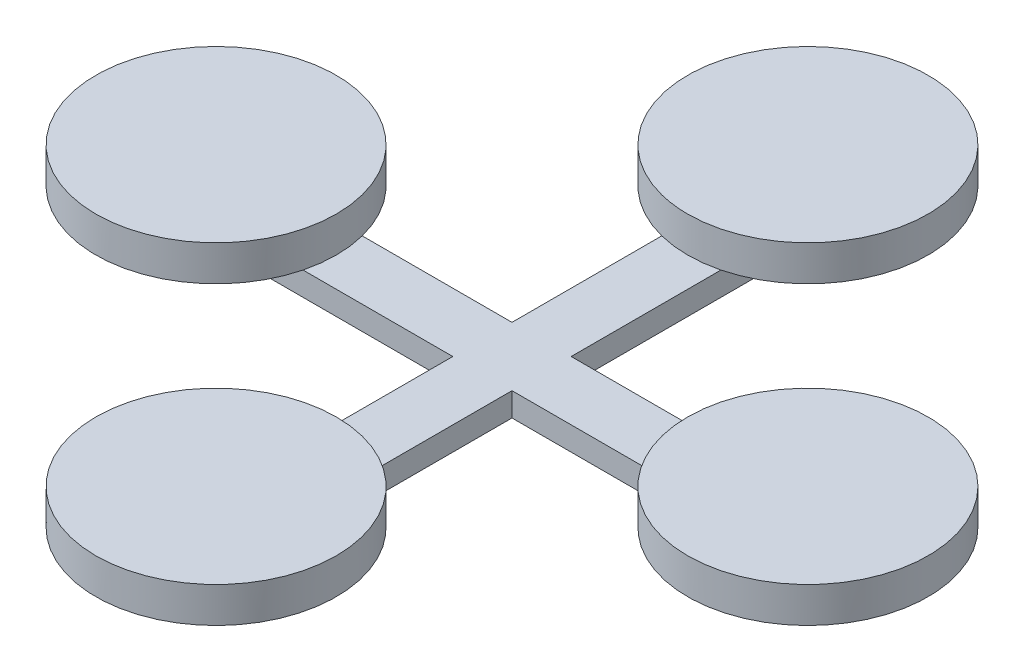
SolidWorks part; units mm, degrees
ref_plane "Front Plane" through (0, 0, 0) normal (0, 0, 1) x (1, 0, 0)
ref_plane "Top Plane" through (0, 0, 0) normal (0, 1, 0) x (1, 0, 0)
ref_plane "Right Plane" through (0, 0, 0) normal (1, 0, 0) x (0, 0, -1)
sketch "Sketch1" plane through (0, 0, 0) normal (0, 1, 0) x (1, 0, 0)
  line L1 (-12.5, 125) -> (12.5, 125)
  line L2 (-12.5, 125) -> (-12.5, -125)
  line L3 (-12.5, -125) -> (12.5, -125)
  line L4 (12.5, 125) -> (12.5, -125)
  line L5 (-12.5, 125) -> (12.5, -125) construction
  line L6 (-12.5, -125) -> (12.5, 125) construction
  line L7 (-125, 12.5) -> (125, 12.5)
  line L8 (-125, 12.5) -> (-125, -12.5)
  line L9 (-125, -12.5) -> (125, -12.5)
  line L10 (125, 12.5) -> (125, -12.5)
  line L11 (-125, 12.5) -> (125, -12.5) construction
  line L12 (-125, -12.5) -> (125, 12.5) construction
  point P0 (0, 0)
  point P6 (0, 0)
  dimension "D1" = 250
  dimension "D2" = 250
  dimension "D3" = 25
extrude "Boss-Extrude1" add sketch "Sketch1" along normal blind 10 contours L2 L7 L4 L1 | L2 L9 L4 L7 | L9 L2 L3 L4 | L10 L7 L4 L9 | L8 L9 L2 L7
sketch "Sketch2" plane through (0, 10, 0) normal (0, 1, 0) x (1, 0, 0)
  line L0 (-12.5, 125) -> (12.5, 125) construction
  line L1 (0, 0) -> (0, 125) construction
  circle A0 centre (0, 125) radius 50.8
  circle A1 centre (125, 0) radius 50.8
  circle A2 centre (0, -125) radius 50.8
  circle A3 centre (-125, 0) radius 50.8
  dimension "D1" = 101.6
  dimension "D3" = 125
  dimension "D2" = 4
extrude "Boss-Extrude2" add sketch "Sketch2" along normal blind 15
